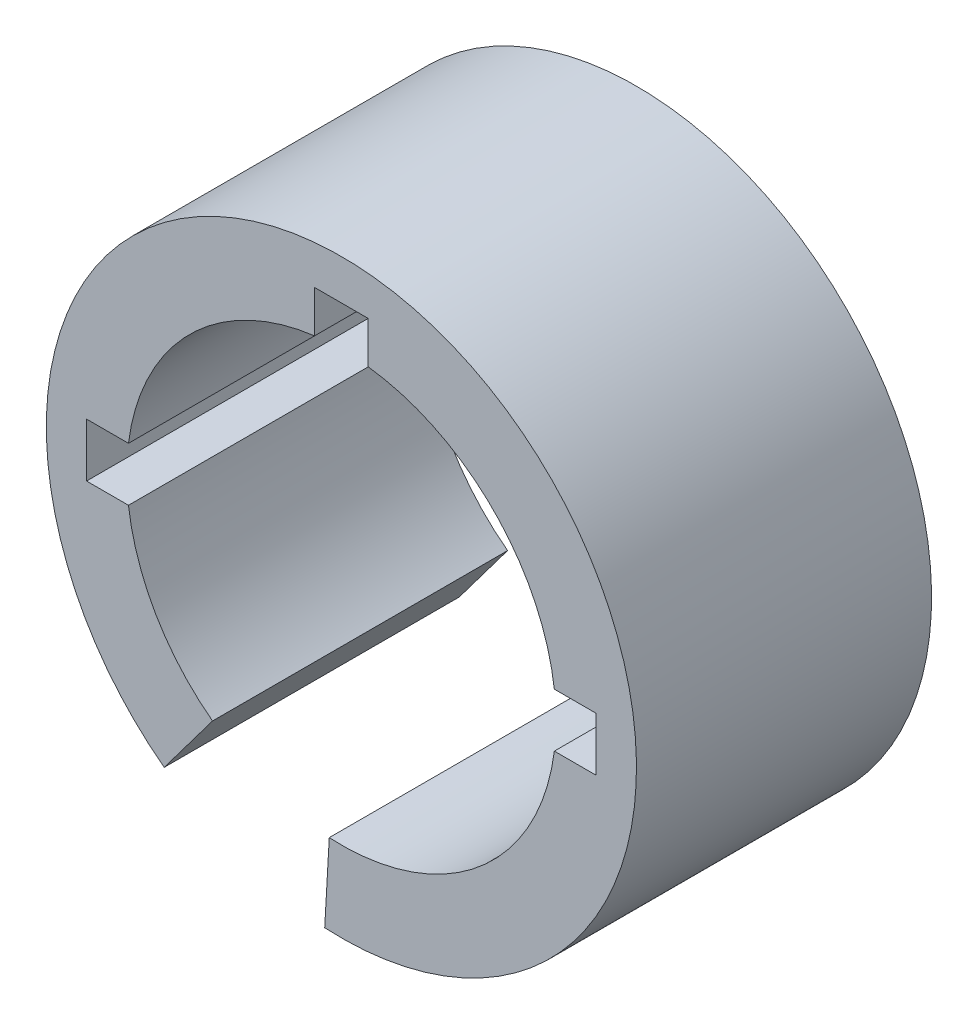
SolidWorks part; units mm, degrees
ref_plane "Front Plane" through (0, 0, 0) normal (0, 0, 1) x (1, 0, 0)
ref_plane "Top Plane" through (0, 0, 0) normal (0, 1, 0) x (1, 0, 0)
ref_plane "Right Plane" through (0, 0, 0) normal (1, 0, 0) x (0, 0, -1)
sketch "Sketch1" plane through (0, 0, 0) normal (0, 0, 1) x (1, 0, 0)
  line L2 (-0.2262, -3.9936) -> (-0.3111, -5.4912)
  line L3 (-2.4019, -3.1985) -> (-3.3027, -4.398)
  arc A2 (-0.2262, -3.9936) -> (-2.4019, -3.1985) centre (0, 0) ccw
  arc A3 (-0.3111, -5.4912) -> (-3.3027, -4.398) centre (0, 0) ccw
extrude "Boss-Extrude1" add sketch "Sketch1" along normal blind 5.5
sketch "Sketch2" plane through (0, 0, 5.5) normal (0, 0, 1) x (1, 0, 0)
  line L1 (-4.75, 0.5) -> (4.75, 0.5)
  line L2 (-4.75, 0.5) -> (-4.75, -0.5)
  line L3 (-4.75, -0.5) -> (4.75, -0.5)
  line L4 (4.75, 0.5) -> (4.75, -0.5)
  line L5 (-4.75, 0.5) -> (4.75, -0.5) construction
  line L6 (-4.75, -0.5) -> (4.75, 0.5) construction
  line L8 (-0.5, -0.5) -> (-0.5, 4.75)
  line L9 (-0.5, 4.75) -> (0.5, 4.75)
  line L10 (0.5, -0.5) -> (0.5, 4.75)
  line L11 (-0.0526, -0.5) -> (0.5, 4.75) construction
  line L12 (-0.5, 4.75) -> (0.0526, -0.5) construction
  point P0 (0, 0)
  point P6 (0, 0)
  arc M6 (-2.4019, -3.1985) -> (-0.2262, -3.9936) centre (0, 0) cw
  dimension "D1" = 1
  dimension "D2" = 9.5
  dimension "D3" = 1
  dimension "D4" = 5.25
extrude "Cut-Extrude1" cut sketch "Sketch2" against normal blind 5.5 contours L10 L9 L8 M6 | L2 L3 L1 M6 | L4 L1 L3 M6
